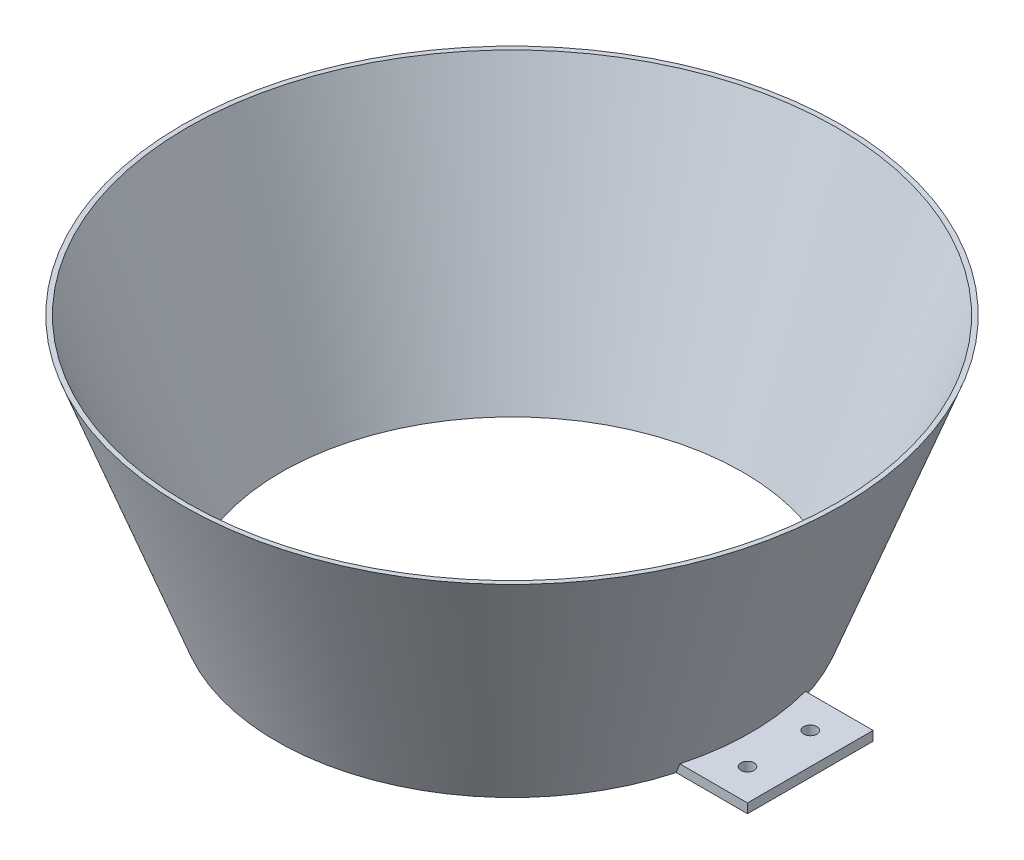
SolidWorks part; units mm, degrees
ref_plane "Front Plane" through (0, 0, 0) normal (0, 0, 1) x (1, 0, 0)
ref_plane "Top Plane" through (0, 0, 0) normal (0, 1, 0) x (1, 0, 0)
ref_plane "Right Plane" through (0, 0, 0) normal (1, 0, 0) x (0, 0, -1)
sketch "Sketch1" plane through (0, 0, 0) normal (0, 0, 1) x (1, 0, 0)
  line L0 (73.5, 0) -> (75, 0)
  line L1 (75, 0) -> (105, 80)
  line L2 (105, 80) -> (103.5, 80)
  line L3 (103.5, 80) -> (73.5, 0)
  line L4 (0, 0) -> (0, 73.1353) construction
  dimension "D1" = 1.5
  dimension "D2" = 73.5
  dimension "D3" = 1.5
  dimension "D4" = 80
  dimension "D5" = 30
revolve "Revolve1" add sketch "Sketch1" angle 360 about L4
sketch "Sketch2" plane through (0, 0, 0) normal (0, -1, 0) x (1, 0, 0)
  line L0 (72.2842, -20) -> (95, -20)
  line L1 (95, -20) -> (95, 20)
  line L2 (95, 20) -> (72.2842, 20)
  line L3 (0, 30.5442) -> (0, -50.5004) construction
  line L4 (-95, 20) -> (-72.2842, 20)
  line L5 (-95, -20) -> (-95, 20)
  line L6 (-72.2842, -20) -> (-95, -20)
  arc A0 (72.2842, 20) -> (72.2842, -20) centre (0, 0) cw
  circle A1 centre (0, 0) radius 75 construction
  arc A3 (-72.2842, 20) -> (-72.2842, -20) centre (0, 0) ccw
  dimension "D1" = 40
  dimension "D2" = 20
  dimension "D3" = 95
extrude "Boss-Extrude1" add sketch "Sketch2" against normal blind 3
sketch "Sketch3" plane through (0, 0, 0) normal (0, -1, 0) x (1, 0, 0)
  line L0 (-27.924, 0) -> (44.9048, 0) construction
  line L1 (0, 29.7164) -> (0, -26.1316) construction
  circle A0 centre (85, 10) radius 2.1
  circle A1 centre (85, -10) radius 2.1
  circle A2 centre (-85, -10) radius 2.1
  circle A3 centre (-85, 10) radius 2.1
  dimension "D1" = 4.2
  dimension "D2" = 85
  dimension "D3" = 10
extrude "Cut-Extrude1" cut sketch "Sketch3" against normal blind 3
